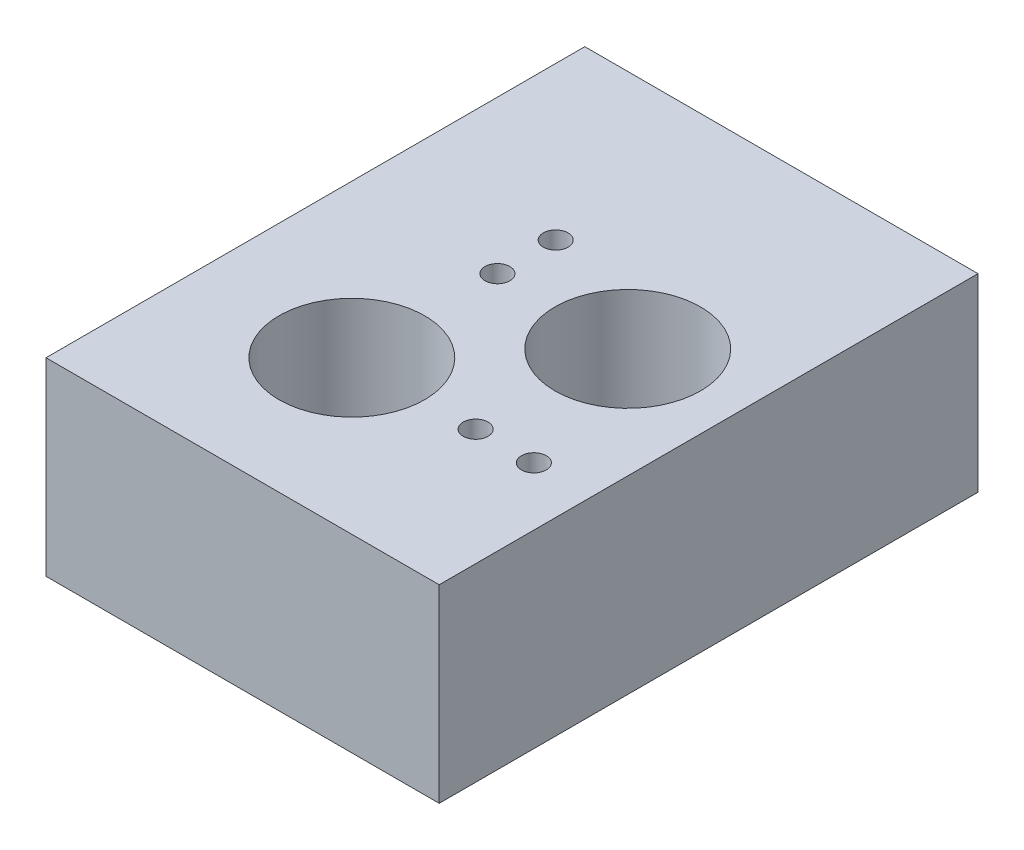
SolidWorks part; units mm, degrees
ref_plane "Front Plane" through (0, 0, 0) normal (0, 0, 1) x (1, 0, 0)
ref_plane "Top Plane" through (0, 0, 0) normal (0, 1, 0) x (1, 0, 0)
ref_plane "Right Plane" through (0, 0, 0) normal (1, 0, 0) x (0, 0, -1)
sketch "Sketch1" plane through (0, 0, 0) normal (0, 1, 0) x (1, 0, 0)
  line L1 (-27, 27) -> (27, 27)
  line L2 (-27, 27) -> (-27, -27)
  line L3 (-27, -27) -> (27, -27)
  line L4 (27, 27) -> (27, -27)
  line L5 (-27, 27) -> (27, -27) construction
  line L6 (-27, -27) -> (27, 27) construction
  point P0 (0, 0)
  dimension "D1" = 54
  dimension "D2" = 54
extrude "Boss-Extrude1" add sketch "Sketch1" along normal blind 26
sketch "Sketch2" plane through (0, 26, 0) normal (0, 1, 0) x (1, 0, 0)
  circle A0 centre (-6, 22) radius 1.7036
  circle A1 centre (-6, 14) radius 1.7036
  circle A2 centre (19, -5.9966) radius 1.7036
  circle A3 centre (11, -5.9966) radius 1.7036
  circle A4 centre (11.8965, 14) radius 10
  circle A5 centre (-6, -5.9966) radius 10
  point P12 (0, 0)
  point P14 (0, 0)
  dimension "D6" = 20
  dimension "D1" = 33
  dimension "D2" = 5
  dimension "D3" = 8
  dimension "D4" = 8
  dimension "D5" = 8
extrude "Cut-Extrude1" cut sketch "Sketch2" against normal through all
sketch "Sketch3" plane through (0, 0, -27) normal (0, 0, -1) x (-1, 0, 0)
  line L4 (-27, 0) -> (27, 0)
  line L5 (27, 0) -> (27, 26)
  line L6 (27, 26) -> (-27, 26)
  line L7 (-27, 26) -> (-27, 0)
  line L8 (-27, 0) -> (27, 0)
  line L9 (27, 0) -> (27, 26)
  line L10 (27, 26) -> (-27, 26)
  line L11 (-27, 26) -> (-27, 0)
  dimension "D1" = 0
extrude "Boss-Extrude2" add sketch "Sketch3" along normal blind 20
sketch "Sketch4" plane through (0, 0, -47) normal (0, 0, -1) x (-1, 0, 0)
  line L1 (-4, 17) -> (16, 17)
  line L2 (-4, 17) -> (-4, 6)
  line L3 (-4, 6) -> (16, 6)
  line L4 (16, 17) -> (16, 6)
  dimension "D1" = 11
  dimension "D2" = 20
  dimension "D3" = 23
  dimension "D4" = 6
extrude "Cut-Extrude2" cut sketch "Sketch4" against normal blind 20
